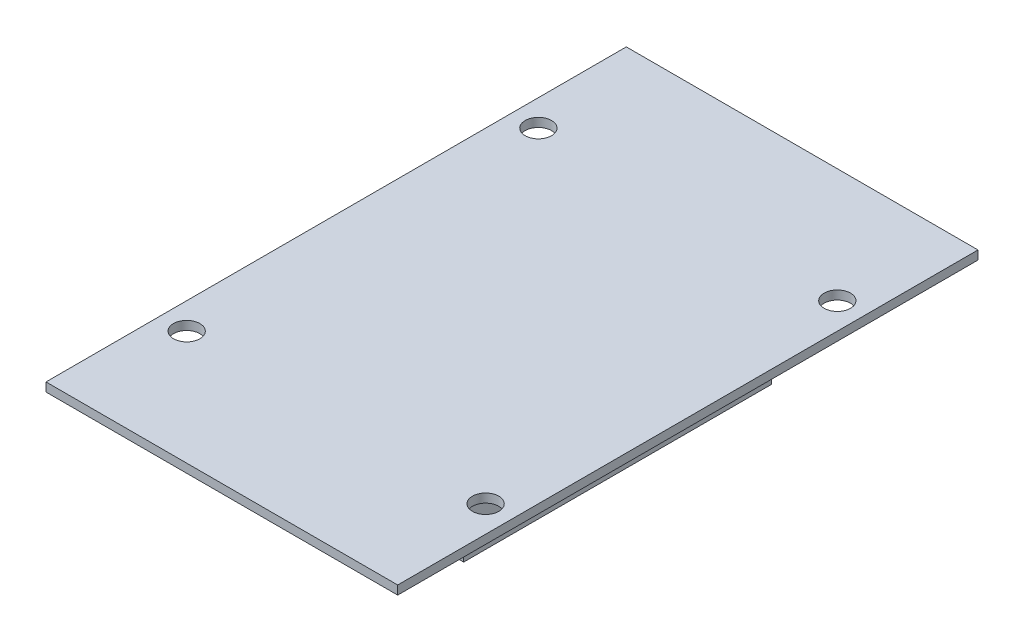
SolidWorks part; units mm, degrees
ref_plane "正面" through (0, 0, 0) normal (0, 0, 1) x (1, 0, 0)
ref_plane "平面" through (0, 0, 0) normal (0, 1, 0) x (1, 0, 0)
ref_plane "右側面" through (0, 0, 0) normal (1, 0, 0) x (0, 0, -1)
sketch "ｽｹｯﾁ1" plane through (0, 0, 0) normal (0, 0, 1) x (1, 0, 0)
  line L1 (0, 0) -> (40, 0)
  line L2 (0, 0) -> (0, 1)
  line L3 (0, 1) -> (40, 1)
  line L4 (40, 0) -> (40, 1)
  dimension "D1" = 1
  dimension "D2" = 40
extrude "ﾎﾞｽ - 押し出し1" add sketch "ｽｹｯﾁ1" along normal blind 66
sketch "ｽｹｯﾁ2" plane through (0, 0, 0) normal (0, -1, 0) x (1, 0, 0)
  line L0 (0, 66) -> (40, 0) construction
  line L1 (40, 66) -> (0, 0) construction
  line L3 (8, 15.5) -> (32, 15.5)
  line L4 (8, 15.5) -> (8, 50.5)
  line L5 (8, 50.5) -> (32, 50.5)
  line L6 (32, 15.5) -> (32, 50.5)
  line L7 (8, 15.5) -> (32, 50.5) construction
  line L8 (8, 50.5) -> (32, 15.5) construction
  point P8 (20, 33)
  dimension "D1" = 24
  dimension "D2" = 35
extrude "ﾎﾞｽ - 押し出し2" add sketch "ｽｹｯﾁ2" along normal blind 8.5
sketch "ｽｹｯﾁ3" plane through (0, 1, 0) normal (0, 1, 0) x (1, 0, 0)
  line L0 (3, -13) -> (3, -53) construction
  line L1 (3, -53) -> (37, -53) construction
  line L2 (37, -53) -> (37, -13) construction
  line L3 (37, -13) -> (3, -13) construction
  line L6 (40, 0) -> (0, 0) construction
  line L8 (20, -13) -> (20, 0) construction
  line L9 (3, -33) -> (0, -33) construction
  line L10 (0, -66) -> (0, 0) construction
  circle A0 centre (3, -13) radius 1.5
  circle A1 centre (37, -13) radius 1.5
  circle A2 centre (3, -53) radius 1.5
  circle A3 centre (37, -53) radius 1.5
  dimension "D5" = 3
  dimension "D1" = 34
  dimension "D2" = 40
extrude "ｶｯﾄ - 押し出し1" cut sketch "ｽｹｯﾁ3" against normal through all
